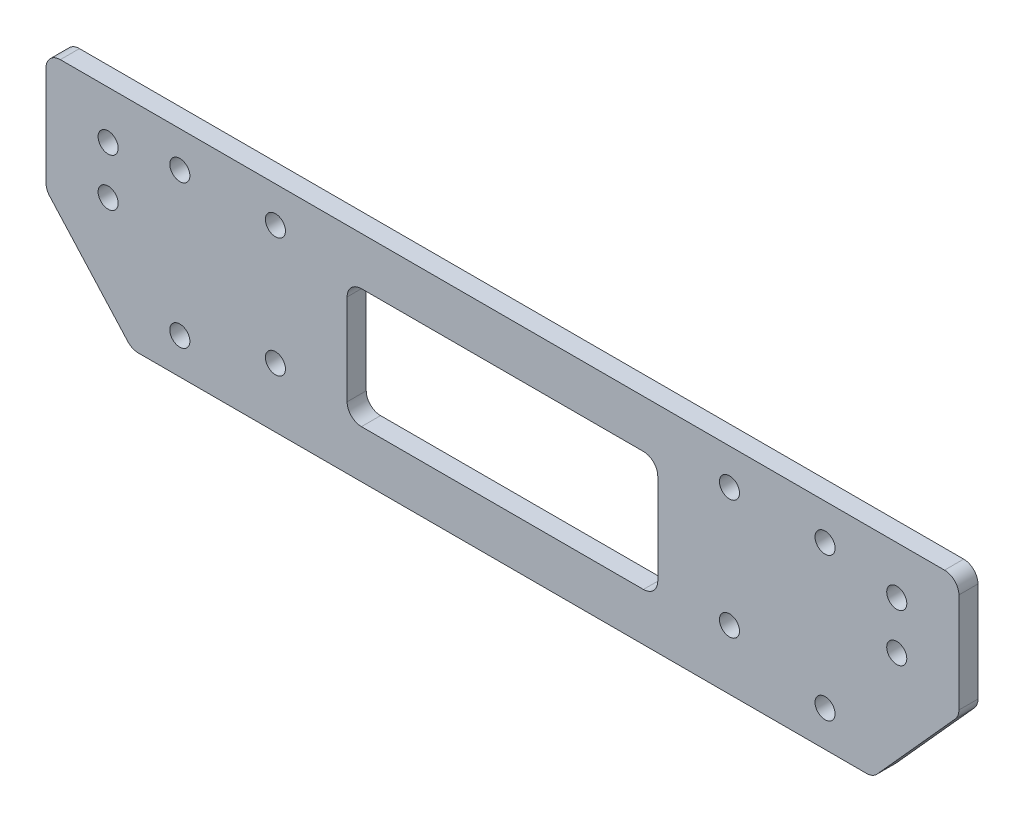
SolidWorks part; units mm, degrees
material "Thornel Mat VMA"
ref_plane "前视基准面" through (0, 0, 0) normal (0, 0, 1) x (1, 0, 0)
ref_plane "上视基准面" through (0, 0, 0) normal (0, 1, 0) x (1, 0, 0)
ref_plane "右视基准面" through (0, 0, 0) normal (1, 0, 0) x (0, 0, -1)
sketch "草图1" plane through (0, 0, 0) normal (0, 0, 1) x (1, 0, 0)
  line L0 (0, 0) -> (0, -41.0741) construction
  line L1 (-77.5, -22.5) -> (77.5, -22.5)
  line L2 (-77.5, -22.5) -> (-77.5, 22.5)
  line L3 (-77.5, 22.5) -> (77.5, 22.5)
  line L4 (77.5, -22.5) -> (77.5, 22.5)
  line L5 (-77.5, -22.5) -> (77.5, 22.5) construction
  line L6 (-77.5, 22.5) -> (77.5, -22.5) construction
  line L7 (-67.5, -15) -> (67.5, -15) construction
  line L8 (-67.5, -15) -> (-67.5, 15) construction
  line L9 (-67.5, 15) -> (67.5, 15) construction
  line L10 (67.5, -15) -> (67.5, 15) construction
  line L12 (-47.5, -10) -> (47.5, -10) construction
  line L13 (-47.5, -10) -> (-47.5, 15) construction
  line L14 (-47.5, 15) -> (47.5, 15) construction
  line L15 (47.5, -10) -> (47.5, 15) construction
  circle A0 centre (-67.5, 15) radius 2.1
  circle A1 centre (-67.5, -15) radius 2.1
  circle A2 centre (67.5, 15) radius 2.1
  circle A3 centre (67.5, -15) radius 2.1
  circle A4 centre (-47.5, 15) radius 2.1
  circle A5 centre (47.5, 15) radius 2.1
  circle A6 centre (-47.5, -10) radius 2.1
  circle A7 centre (47.5, -10) radius 2.1
  point P0 (0, 0)
  dimension "D6" = 4.2
  dimension "D1" = 155
  dimension "D2" = 135
  dimension "D3" = 7.5
  dimension "D4" = 30
  dimension "D5" = 7.5
  dimension "D7" = 25
  dimension "D8" = 95
extrude "凸台-拉伸1" add sketch "草图1" along normal blind 4
sketch "草图2" plane through (0, 0, 4) normal (0, 0, 1) x (1, 0, 0)
  line L0 (77.5, 22.5) -> (-77.5, 22.5) construction
  line L1 (-32.5, -12.5) -> (32.5, -12.5)
  line L2 (-32.5, -12.5) -> (-32.5, 12.5)
  line L3 (-32.5, 12.5) -> (32.5, 12.5)
  line L4 (32.5, -12.5) -> (32.5, 12.5)
  line L5 (-32.5, -12.5) -> (32.5, 12.5) construction
  line L6 (-32.5, 12.5) -> (32.5, -12.5) construction
  line L8 (77.5, -22.5) -> (77.5, 22.5) construction
  point P0 (0, 0)
  dimension "D1" = 10
  dimension "D2" = 45
extrude "切除-拉伸1" cut sketch "草图2" against normal blind 10
sketch "草图3" plane through (0, 0, 4) normal (0, 0, 1) x (1, 0, 0)
  line L0 (-77.5, 22.5) -> (-95.5, 22.5)
  line L1 (-95.5, 22.5) -> (-95.5, -2.5)
  line L2 (-95.5, -2.5) -> (-77.5, -22.5)
  line L3 (-77.5, 22.5) -> (-77.5, -22.5)
  line L4 (-82.5, 12.5) -> (-82.5, 2.5) construction
  line L5 (0, 0) -> (0, 22.5) construction
  line L6 (77.5, 22.5) -> (-77.5, 22.5) construction
  line L7 (77.5, 22.5) -> (95.5, 22.5)
  line L8 (95.5, 22.5) -> (95.5, -2.5)
  line L9 (95.5, -2.5) -> (77.5, -22.5)
  line L10 (77.5, 22.5) -> (77.5, -22.5)
  circle A0 centre (-82.5, 12.5) radius 2.1
  circle A1 centre (-82.5, 2.5) radius 2.1
  circle A2 centre (82.5, 12.5) radius 2.1
  circle A3 centre (82.5, 2.5) radius 2.1
  dimension "D3" = 4.2
  dimension "D5" = 10
  dimension "D1" = 18
  dimension "D2" = 25
  dimension "D4" = 10
  dimension "D6" = 5
extrude "凸台-拉伸2" add sketch "草图3" against normal up to vertex (4 mm away)
fillet "圆角1" radius 3 10 edges at (32.5, -12.5, 2) (-32.5, -12.5, 2) (-32.5, 12.5, 2) (32.5, 12.5, 2) (-95.5, -2.5, 2) (-77.5, -22.5, 2) (77.5, -22.5, 2) (95.5, -2.5, 2) (95.5, 22.5, 2) (-95.5, 22.5, 2)
